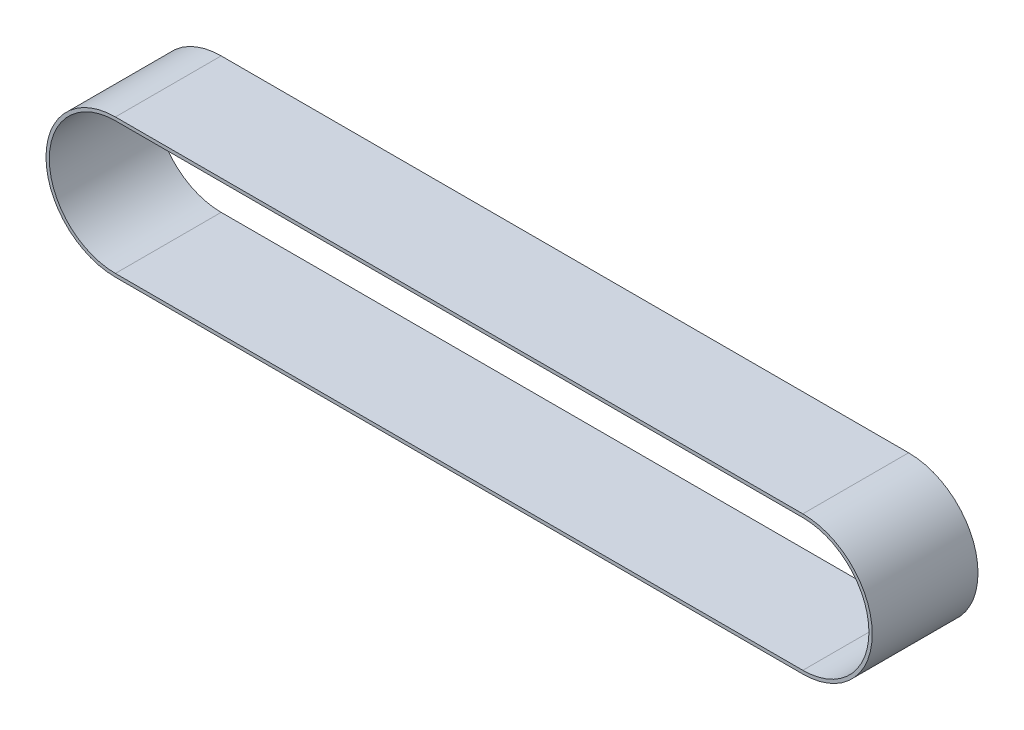
SolidWorks part; units mm, degrees
material "POLYURETHANE (11671)"
ref_plane "Front Plane" through (0, 0, 0) normal (0, 0, 1) x (1, 0, 0)
ref_plane "Top Plane" through (0, 0, 0) normal (0, 1, 0) x (1, 0, 0)
ref_plane "Right Plane" through (0, 0, 0) normal (1, 0, 0) x (0, 0, -1)
sketch "Sketch1" plane through (0, 0, 0) normal (0, 0, 1) x (1, 0, 0)
  line L0 (0, 0) -> (330.2, 0) construction
  line L1 (0, 31.75) -> (330.2, 31.75)
  line L2 (0, -31.75) -> (330.2, -31.75)
  line L3 (0, 0) -> (330.2, 0) construction
  line L4 (0, 33.3375) -> (330.2, 33.3375)
  line L5 (0, -33.3375) -> (330.2, -33.3375)
  arc A0 (0, 31.75) -> (0, -31.75) centre (0, 0) ccw
  arc A1 (330.2, -31.75) -> (330.2, 31.75) centre (330.2, 0) ccw
  arc A2 (0, 33.3375) -> (0, -33.3375) centre (0, 0) ccw
  arc A3 (330.2, -33.3375) -> (330.2, 33.3375) centre (330.2, 0) ccw
  point P3 (165.1, 0)
  point P10 (165.1, 0)
  dimension "D1" = 330.2
  dimension "D2" = 63.5
  dimension "D3" = 66.675
extrude "Boss-Extrude1" add sketch "Sketch1" along normal blind 50.8
